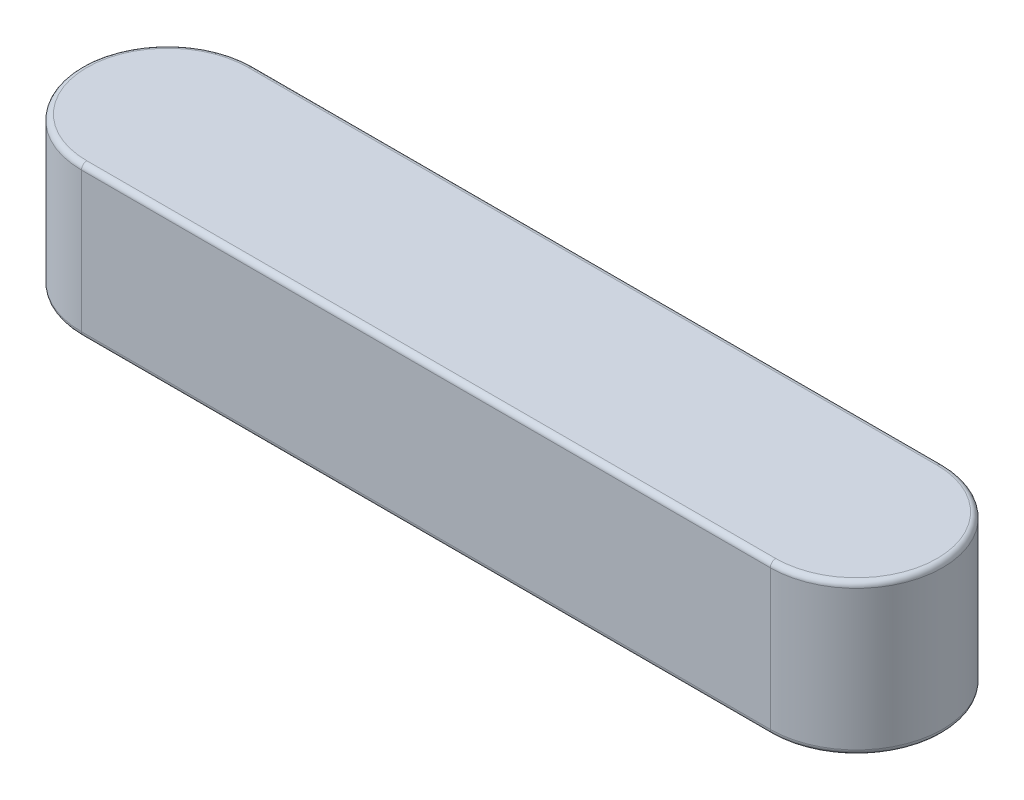
SolidWorks part; units mm, degrees
ref_plane "Front Plane" through (0, 0, 0) normal (0, 0, 1) x (1, 0, 0)
ref_plane "Top Plane" through (0, 0, 0) normal (0, 1, 0) x (1, 0, 0)
ref_plane "Right Plane" through (0, 0, 0) normal (1, 0, 0) x (0, 0, -1)
sketch "Sketch1" plane through (0, 0, 0) normal (0, 1, 0) x (1, 0, 0)
  line L1 (-32, 4) -> (0, 4)
  line L3 (-32, -4) -> (0, -4)
  arc A0 (0, -4) -> (0, 4) centre (0, 0) ccw
  arc A1 (-32, 4) -> (-32, -4) centre (-32, 0) ccw
  dimension "l" = 40
  dimension "b" = 8
extrude "Extrude1" add sketch "Sketch1" along normal blind 7
fillet "Fillet1" radius 0.25 8 edges at (-16, 0, -4) (4, 0, 0) (-36, 0, 0) (-16, 0, 4) (4, 7, 0) (-16, 7, 4) (-16, 7, -4) (-36, 7, 0)
